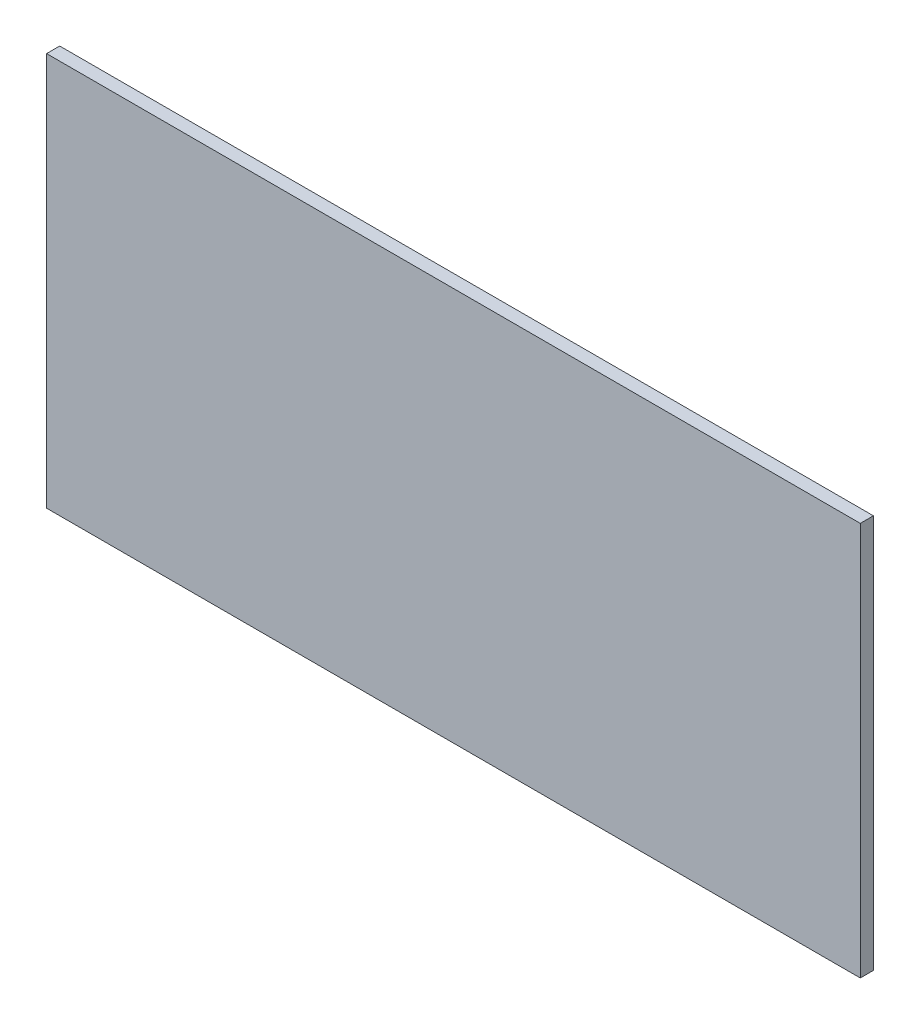
SolidWorks part; units mm, degrees
ref_plane "Front Plane" through (0, 0, 0) normal (0, 0, 1) x (1, 0, 0)
ref_plane "Top Plane" through (0, 0, 0) normal (0, 1, 0) x (1, 0, 0)
ref_plane "Right Plane" through (0, 0, 0) normal (1, 0, 0) x (0, 0, -1)
sketch "Sketch1" plane through (0, 0, 90) normal (0, 0, 1) x (1, 0, 0)
  line L1 (-62, 60) -> (62, 60)
  line L2 (-62, 60) -> (-62, 0)
  line L3 (-62, 0) -> (62, 0)
  line L4 (62, 60) -> (62, 0)
extrude "Boss-Extrude1" add sketch "Sketch1" along normal blind 2 contours L1 L4 L3 L2
ref_plane "Plane1" through (62, 60, 92) normal (0, -1, 0) x (-1, 0, 0)
